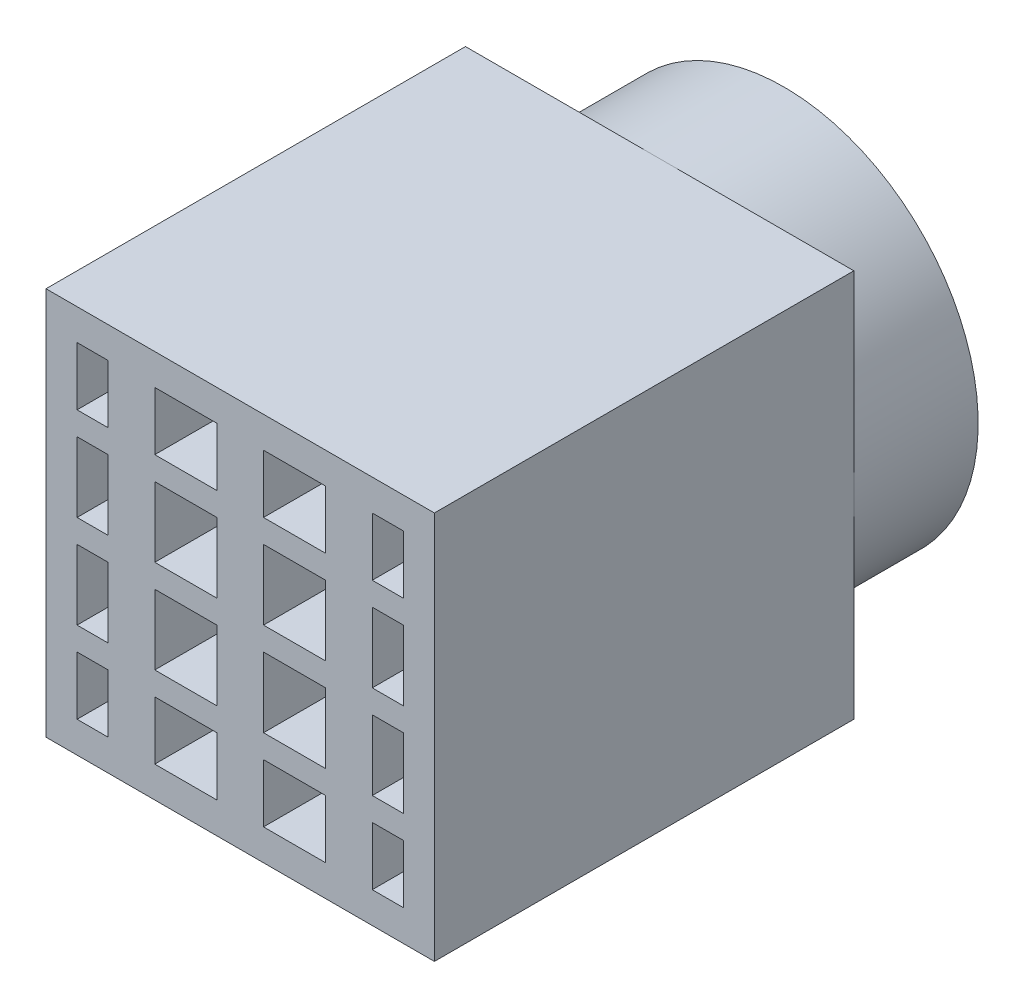
SolidWorks part; units mm, degrees
ref_plane "前视基准面" through (0, 0, 0) normal (0, 0, 1) x (1, 0, 0)
ref_plane "上视基准面" through (0, 0, 0) normal (0, 1, 0) x (1, 0, 0)
ref_plane "右视基准面" through (0, 0, 0) normal (1, 0, 0) x (0, 0, -1)
sketch "草图8" plane through (0, 0, 0) normal (0, 0, 1) x (1, 0, 0)
  line L0 (0, 7.8741) -> (0, -9.2542) construction
  line L1 (-12.5, -12.5) -> (12.5, -12.5)
  line L2 (-12.5, -12.5) -> (-12.5, 12.5)
  line L3 (-12.5, 12.5) -> (12.5, 12.5)
  line L4 (12.5, -12.5) -> (12.5, 12.5)
  line L5 (-12.5, -12.5) -> (12.5, 12.5) construction
  line L6 (-12.5, 12.5) -> (12.5, -12.5) construction
  line L7 (-16.0619, 0) -> (15.5648, 0) construction
  line L8 (-3.5, 7.8741) -> (-3.5, -9.2542) construction
  line L9 (-9.5, 7.8741) -> (-9.5, -9.2542) construction
  line L10 (5.5, 10.5) -> (1.5, 10.5)
  line L15 (-5.5, -10.5) -> (-1.5, -10.5)
  line L20 (-5.5, -10.5) -> (-5.5, 10.5)
  line L21 (-5.5, 10.5) -> (-1.5, 10.5)
  line L26 (-1.5, -10.5) -> (-1.5, 10.5)
  line L27 (-5.5, -10.5) -> (-1.5, 10.5) construction
  line L28 (-5.5, 10.5) -> (-1.5, -10.5) construction
  line L29 (-10.5, -10.5) -> (-8.5, -10.5)
  line L30 (-10.5, -10.5) -> (-10.5, 10.5)
  line L31 (-10.5, 10.5) -> (-8.5, 10.5)
  line L32 (-8.5, -10.5) -> (-8.5, 10.5)
  line L33 (-10.5, -10.5) -> (-8.5, 10.5) construction
  line L34 (-10.5, 10.5) -> (-8.5, -10.5) construction
  line L35 (1.5, -10.5) -> (1.5, 10.5)
  line L36 (5.5, -10.5) -> (1.5, -10.5)
  line L37 (5.5, -10.5) -> (5.5, 10.5)
  line L38 (10.5, 10.5) -> (8.5, 10.5)
  line L39 (8.5, -10.5) -> (8.5, 10.5)
  line L40 (10.5, -10.5) -> (8.5, -10.5)
  line L41 (10.5, -10.5) -> (10.5, 10.5)
  point P0 (0, 0)
  point P14 (-7, 0)
  point P15 (-3.5, 0)
  point P17 (-3, 0)
  point P21 (-9.5, 0)
  point P22 (-9, 0)
  dimension "D1" = 3.5
  dimension "D2" = 6
extrude "凸台-拉伸7" add sketch "草图8" along normal blind 25
sketch "草图9" plane through (0, 0, 0) normal (0, 0, -1) x (-1, 0, 0)
  line L1 (-12.5, -12.5) -> (12.5, -12.5)
  line L2 (-12.5, -12.5) -> (-12.5, 12.5)
  line L3 (-12.5, 12.5) -> (12.5, 12.5)
  line L4 (12.5, -12.5) -> (12.5, 12.5)
  line L5 (-12.5, -12.5) -> (12.5, 12.5) construction
  line L6 (-12.5, 12.5) -> (12.5, -12.5) construction
  point P0 (0, 0)
extrude "凸台-拉伸8" add sketch "草图9" along normal blind 2
sketch "草图14" plane through (0, 0, 25) normal (0, 0, 1) x (1, 0, 0)
  line L0 (-16.6961, 0) -> (20.7273, 0) construction
  line L1 (-12.5, 12.5) -> (-12.5, -12.5) construction
  line L2 (12.5, -0.75) -> (-12.5, -0.75)
  line L3 (12.5, -0.75) -> (12.5, 0.75)
  line L4 (12.5, 0.75) -> (-12.5, 0.75)
  line L5 (-12.5, -0.75) -> (-12.5, 0.75)
  line L6 (12.5, -0.75) -> (-12.5, 0.75) construction
  line L7 (12.5, 0.75) -> (-12.5, -0.75) construction
  line L12 (12.5, 5.25) -> (-12.5, 5.25)
  line L13 (12.5, 5.25) -> (12.5, 6.75)
  line L14 (12.5, 6.75) -> (-12.5, 6.75)
  line L15 (-12.5, 5.25) -> (-12.5, 6.75)
  line L16 (12.5, 5.25) -> (-12.5, 6.75) construction
  line L17 (12.5, 6.75) -> (-12.5, 5.25) construction
  line L18 (12.5, -6.75) -> (-12.5, -5.25) construction
  line L19 (12.5, -5.25) -> (-12.5, -6.75) construction
  line L20 (-12.5, -5.25) -> (-12.5, -6.75)
  line L21 (12.5, -6.75) -> (-12.5, -6.75)
  line L22 (12.5, -5.25) -> (12.5, -6.75)
  line L23 (12.5, -5.25) -> (-12.5, -5.25)
  point P3 (0, 0)
  point P11 (0, 6)
  point P19 (0, -6)
  dimension "D1" = 2
extrude "凸台-拉伸11" add sketch "草图14" against normal blind 25
sketch "草图16" plane through (0, 0, -2) normal (0, 0, -1) x (-1, 0, 0)
  circle A0 centre (0, 0) radius 12.5
  circle A1 centre (0, 0) radius 10
extrude "凸台-拉伸14" add sketch "草图16" along normal blind 6
sketch "草图17" plane through (0, 0, -8) normal (0, 0, -1) x (-1, 0, 0)
  circle A0 centre (0, 0) radius 12.5
extrude "凸台-拉伸15" add sketch "草图17" along normal blind 2
sketch "草图18" plane through (12.5, 0, 0) normal (1, 0, 0) x (0, 0, -1)
  line L0 (-20, 12.5) -> (-20, -12.5)
  line L1 (-25, 12.5) -> (2, 12.5) construction
  line L2 (-25, -12.5) -> (2, -12.5) construction
  line L3 (-25, -12.5) -> (-25, 12.5) construction
  line L4 (-25, -5.9923) -> (2, -5.9923)
  line L5 (2, 0) -> (2, -12.5) construction
  dimension "D1" = 5
sketch "草图19" plane through (-12.5, 0, 0) normal (-1, 0, 0) x (0, 0, 1)
  line L0 (-2, -5.9923) -> (25, -5.9923)
  line L1 (20, 12.5) -> (20, -12.5)
